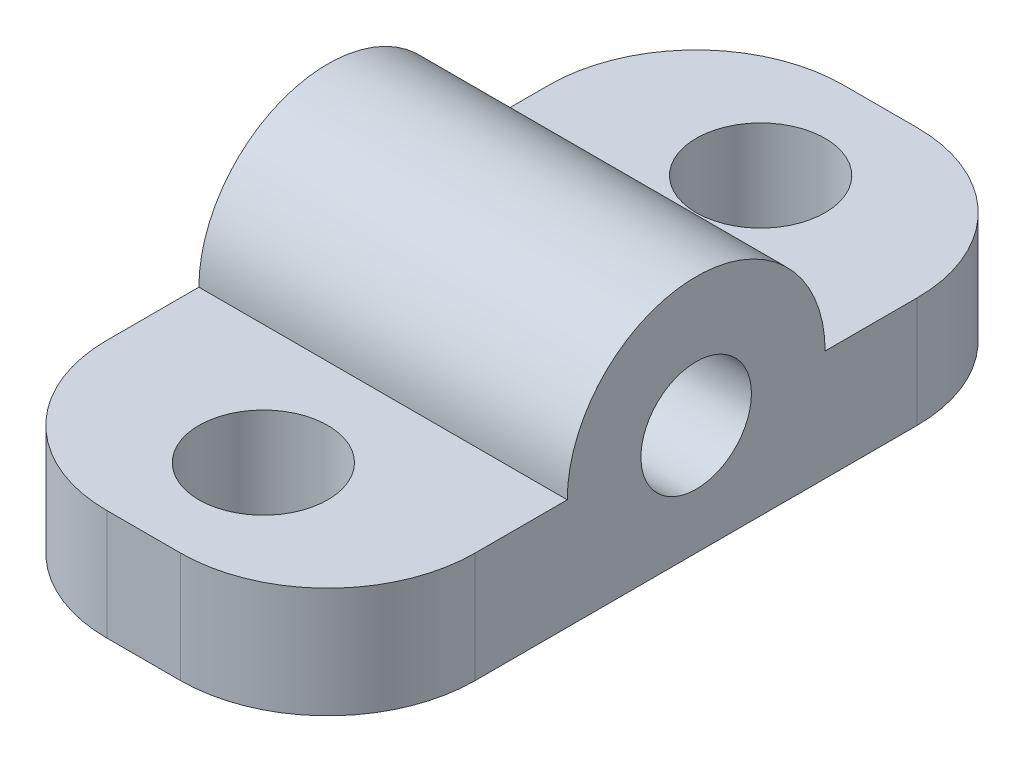
SolidWorks part; units mm, degrees
ref_plane "Спереди" through (0, 0, 0) normal (0, 0, 1) x (1, 0, 0)
ref_plane "Сверху" through (0, 0, 0) normal (0, 1, 0) x (1, 0, 0)
ref_plane "Справа" through (0, 0, 0) normal (1, 0, 0) x (0, 0, -1)
sketch "Эскиз1" plane through (0, 0, 0) normal (1, 0, 0) x (0, 0, -1)
  line L0 (-10, -3) -> (10, -3)
  line L1 (-10, -3) -> (-10, 0)
  line L2 (-10, 0) -> (-3.5, 0)
  line L3 (0, 0) -> (0, -3) construction
  line L4 (3.5, 0) -> (10, 0)
  line L5 (10, 0) -> (10, -3)
  circle A0 centre (0, 0) radius 1.5
  arc A1 (3.5, 0) -> (-3.5, 0) centre (0, 0) ccw
  dimension "D1" = 3
  dimension "D2" = 7
  dimension "D3" = 3
  dimension "D4" = 20
extrude "Бобышка-Вытянуть1" add sketch "Эскиз1" along normal blind 10
sketch "Эскиз2" plane through (0, 0, 0) normal (0, 1, 0) x (1, 0, 0)
  line L0 (0, 6.75) -> (10, 6.75) construction
  line L1 (0, 10) -> (0, 3.5) construction
  line L2 (10, 10) -> (10, 3.5) construction
  line L5 (0, -3.5) -> (0, -10) construction
  line L6 (0, -6.75) -> (10, -6.75) construction
  line L7 (10, -3.5) -> (10, -10) construction
  circle A0 centre (5, 6.75) radius 1.75
  circle A1 centre (5, -6.75) radius 1.75
  dimension "D1" = 3.5
extrude "Вырез-Вытянуть1" cut sketch "Эскиз2" against normal through all
fillet "Скругление2" radius 4 4 edges at (0, -1.5, 10) (10, -1.5, 10) (0, -1.5, -10) (10, -1.5, -10)
